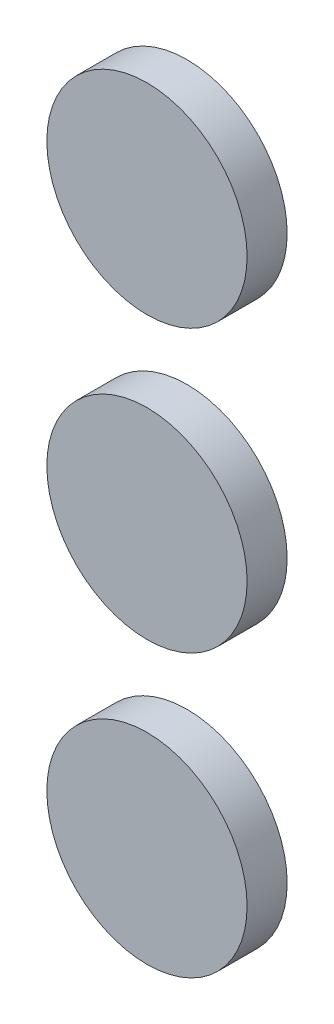
SolidWorks part; units mm, degrees
ref_plane "Plan de face" through (0, 0, 0) normal (0, 0, 1) x (1, 0, 0)
ref_plane "Plan de dessus" through (0, 0, 0) normal (0, 1, 0) x (1, 0, 0)
ref_plane "Plan de droite" through (0, 0, 0) normal (1, 0, 0) x (0, 0, -1)
sketch "Esquisse1" plane through (0, 0, 0) normal (0, 0, 1) x (1, 0, 0)
  ellipse E1 centre (43.9, 54.2423) end of major axis (43.9, 52.988) minor radius 1.25
  ellipse E2 centre (43.9, 54.2423) end of major axis (43.9, 52.988) minor radius 1.25
  ellipse E3 centre (43.9, 57.7545) end of major axis (43.9, 56.5001) minor radius 1.25
  ellipse E4 centre (43.9, 57.7545) end of major axis (43.9, 56.5001) minor radius 1.25
  ellipse E5 centre (43.9, 61.2666) end of major axis (43.9, 62.5209) minor radius 1.25
  ellipse E6 centre (43.9, 61.2666) end of major axis (43.9, 62.5209) minor radius 1.25
  dimension "D1" = 0
  dimension "D2" = 0
  dimension "D3" = 0
extrude "Boss.-Extru.1" add sketch "Esquisse1" along normal blind 0.5
